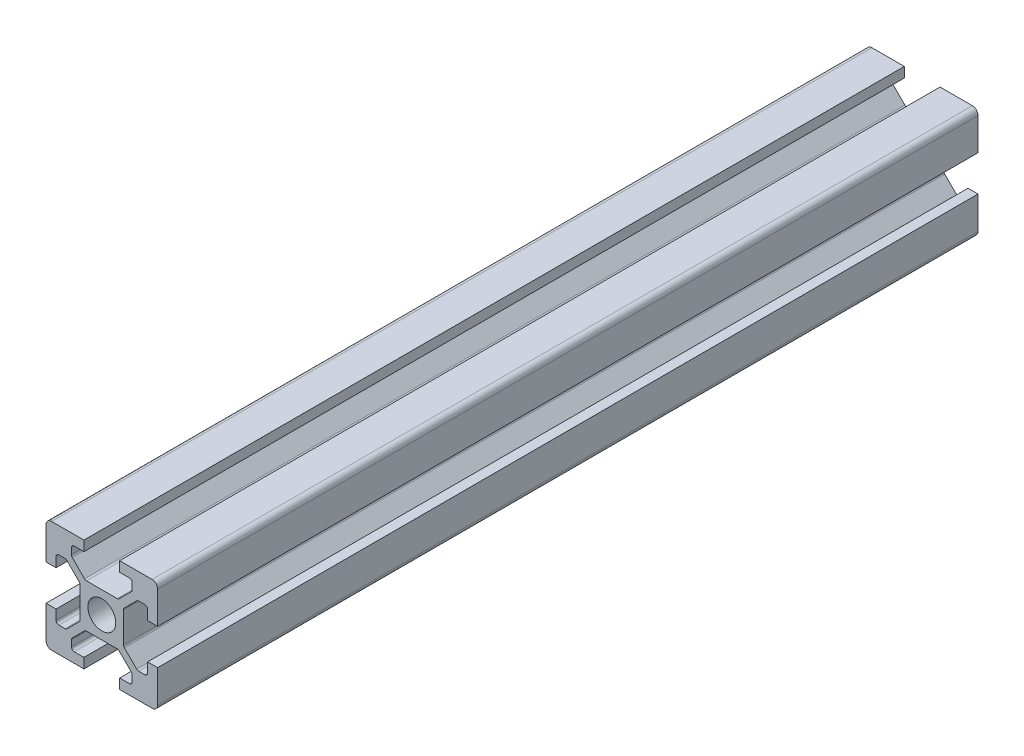
SolidWorks part; units mm, degrees
material "1060 Alloy"
ref_plane "Front Plane" through (0, 0, 0) normal (0, 0, 1) x (1, 0, 0)
ref_plane "Top Plane" through (0, 0, 0) normal (0, 1, 0) x (1, 0, 0)
ref_plane "Right Plane" through (0, 0, 0) normal (1, 0, 0) x (0, 0, -1)
sketch "Sketch1" plane through (0, 0, 0) normal (0, 0, 1) x (1, 0, 0)
  line L0 (20, 0) -> (-8.059, 28.059) construction
  line L1 (0, 0) -> (6.8, 0)
  line L2 (0, 0) -> (0, 6.8)
  line L3 (0, 20) -> (6.8, 20)
  line L4 (20, 0) -> (20, 6.8)
  line L5 (6.8, 20) -> (6.8, 18.2)
  line L6 (20, 20) -> (8.2322, 8.2322) construction
  line L7 (12.95, 6.1) -> (7.05, 6.1)
  line L8 (13.9, 7.05) -> (13.9, 12.95)
  line L9 (12.95, 13.9) -> (7.05, 13.9)
  line L10 (6.1, 7.05) -> (6.1, 12.95)
  line L11 (13.9, 6.1) -> (6.1, 13.9) construction
  line L12 (13.9, 13.9) -> (6.1, 6.1) construction
  line L13 (4.55, 16.4) -> (7.05, 13.9)
  line L14 (13.2, 18.2) -> (13.2, 20)
  line L15 (1.8, 6.8) -> (0, 6.8)
  line L16 (0, 13.2) -> (0, 20)
  line L17 (0, 13.2) -> (1.8, 13.2)
  line L18 (10, 10) -> (10, 13.9) construction
  line L19 (16.4, 4.55) -> (13.9, 7.05)
  line L20 (4.55, 16.4) -> (4.55, 18.2)
  line L21 (4.55, 18.2) -> (6.8, 18.2)
  line L22 (13.2, 18.2) -> (15.45, 18.2)
  line L23 (15.45, 18.2) -> (15.45, 16.4)
  line L24 (15.45, 16.4) -> (12.95, 13.9)
  line L25 (16.4, 4.55) -> (18.2, 4.55)
  line L26 (18.2, 4.55) -> (18.2, 6.8)
  line L27 (20, 6.8) -> (18.2, 6.8)
  line L28 (18.2, 13.2) -> (20, 13.2)
  line L29 (18.2, 13.2) -> (18.2, 15.45)
  line L30 (18.2, 15.45) -> (16.4, 15.45)
  line L31 (16.4, 15.45) -> (13.9, 12.95)
  line L32 (1.8, 4.55) -> (3.6, 4.55)
  line L33 (3.6, 15.45) -> (6.1, 12.95)
  line L34 (3.6, 15.45) -> (1.8, 15.45)
  line L35 (1.8, 15.45) -> (1.8, 13.2)
  line L36 (0, 13.2) -> (1.8, 13.2)
  line L37 (1.8, 6.8) -> (0, 6.8)
  line L38 (3.6, 4.55) -> (6.1, 7.05)
  line L39 (1.8, 6.8) -> (1.8, 4.55)
  line L40 (15.45, 3.6) -> (12.95, 6.1)
  line L41 (4.55, 3.6) -> (7.05, 6.1)
  line L42 (4.55, 1.8) -> (4.55, 3.6)
  line L43 (6.8, 1.8) -> (4.55, 1.8)
  line L44 (6.8, 1.8) -> (6.8, 0)
  line L45 (15.45, 3.6) -> (15.45, 1.8)
  line L46 (15.45, 1.8) -> (13.2, 1.8)
  line L47 (13.2, 0) -> (13.2, 1.8)
  line L48 (13.2, 20) -> (20, 20)
  line L49 (20, 13.2) -> (20, 20)
  line L50 (13.2, 0) -> (20, 0)
  line L51 (6.1, 6.1) -> (-5.5045, -5.5045) construction
  circle A0 centre (10, 10) radius 2.5
  point P25 (10, 16.4)
  point P39 (13.2, 19.1)
  point P46 (0.9, 6.8)
  dimension "D3" = 5
  dimension "D2" = 20
  dimension "D4" = 7.8
  dimension "D5" = 7.8
  dimension "D6" = 6.8
  dimension "D7" = 6.8
  dimension "D8" = 1.8
  dimension "D9" = 10.9
  dimension "D10" = 1.8
  dimension "D11" = 10.9
  dimension "D12" = 20
extrude "Boss-Extrude1" add sketch "Sketch1" along normal blind 147 contours L47 L50 L4 L27 L26 L25 L19 L8 L31 L30 L29 L28 L49 L48 L14 L22 L23 L24 L9 L13 L20 L21 L5 L3 L16 L17 L35 L34 L33 L10 L38 L32 L39 L15 L2 L1 L44 L43 L42 L41 L7 L40 L45 L46 A0
fillet "Fillet1" radius 1 4 edges at (20, 20, 73.5) (20, 0, 73.5) (0, 0, 73.5) (0, 20, 73.5)
fillet "Fillet2" radius 0.5 6 edges at (4.55, 18.2, 73.5) (4.55, 16.4, 73.5) (7.05, 13.9, 73.5) (15.45, 18.2, 73.5) (15.45, 16.4, 73.5) (12.95, 13.9, 73.5)
fillet "Fillet3" radius 0.5 6 edges at (18.2, 15.45, 73.5) (16.4, 15.45, 73.5) (13.9, 12.95, 73.5) (18.2, 4.55, 73.5) (13.9, 7.05, 73.5) (16.4, 4.55, 73.5)
fillet "Fillet4" radius 0.5 6 edges at (1.8, 15.45, 73.5) (3.6, 15.45, 73.5) (6.1, 12.95, 73.5) (3.6, 4.55, 73.5) (1.8, 4.55, 73.5) (6.1, 7.05, 73.5)
fillet "Fillet5" radius 0.5 6 edges at (7.05, 6.1, 73.5) (4.55, 3.6, 73.5) (4.55, 1.8, 73.5) (15.45, 1.8, 73.5) (15.45, 3.6, 73.5) (12.95, 6.1, 73.5)
